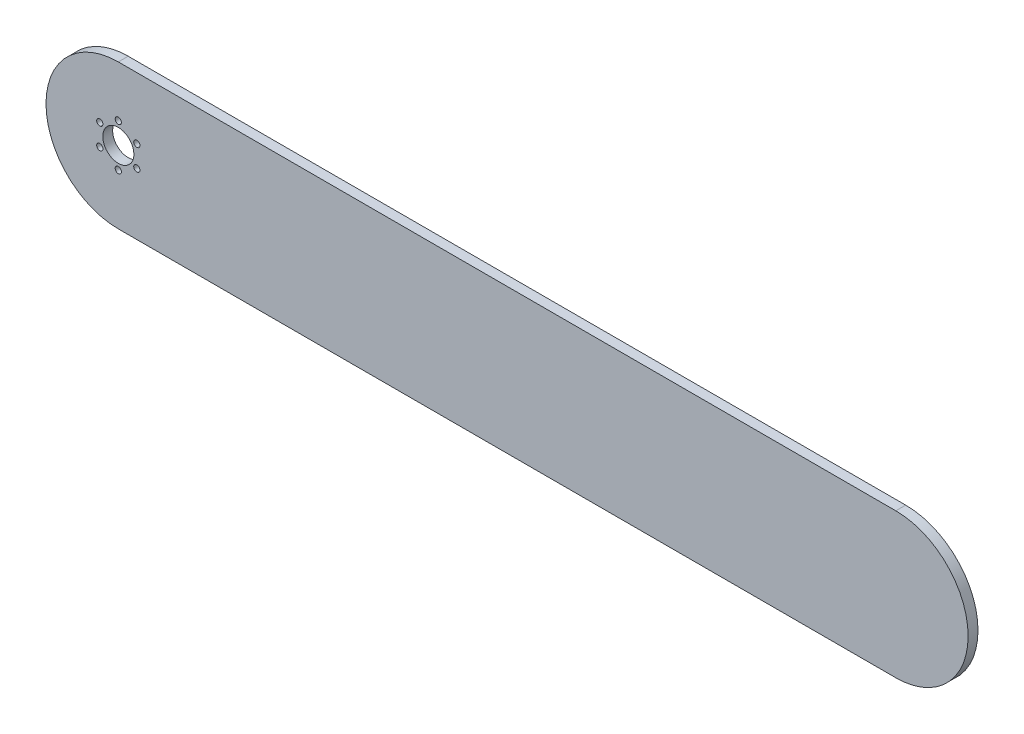
SolidWorks part; units mm, degrees
ref_plane "Front Plane" through (0, 0, 0) normal (0, 0, 1) x (1, 0, 0)
ref_plane "Top Plane" through (0, 0, 0) normal (0, 1, 0) x (1, 0, 0)
ref_plane "Right Plane" through (0, 0, 0) normal (1, 0, 0) x (0, 0, -1)
sketch "Sketch2" plane through (0, 0, 0) normal (0, 0, 1) x (1, 0, 0)
  line L0 (0, 0) -> (500, 0) construction
  line L1 (0, 46.5) -> (500, 46.5)
  line L2 (0, -46.5) -> (500, -46.5)
  arc A0 (0, 46.5) -> (0, -46.5) centre (0, 0) ccw
  arc A1 (500, -46.5) -> (500, 46.5) centre (500, 0) ccw
  circle A2 centre (500, 0) radius 37.25 construction
  circle A3 centre (0, 0) radius 10
  circle A4 centre (0, 13.75) radius 2
  circle A5 centre (0, 0) radius 13.75 construction
  circle A6 centre (11.9078, 6.875) radius 2
  circle A7 centre (11.9078, -6.875) radius 2
  circle A8 centre (0, -13.75) radius 2
  circle A9 centre (-11.9078, -6.875) radius 2
  circle A10 centre (-11.9078, 6.875) radius 2
  point P3 (250, 0)
  point P27 (0, 0)
  dimension "D2" = 74.5
  dimension "D4" = 20
  dimension "D5" = 4
  dimension "D6" = 27.5
  dimension "D3" = 46.5
  dimension "D1" = 500
  dimension "D7" = 6
extrude "Boss-Extrude1" add sketch "Sketch2" along normal blind 6.35
equation "\"L1L\"=500"
equation "\"L1Thick\"=6.35"
equation "\"D1@Sketch2\"=\"L1L\""
equation "\"Harm-Drive-Outer\"=74.5"
equation "\"D2@Sketch2\"=\"Harm-Drive-Outer\""
equation "\"D1@Boss-Extrude1\"=\"L1Thick\""
